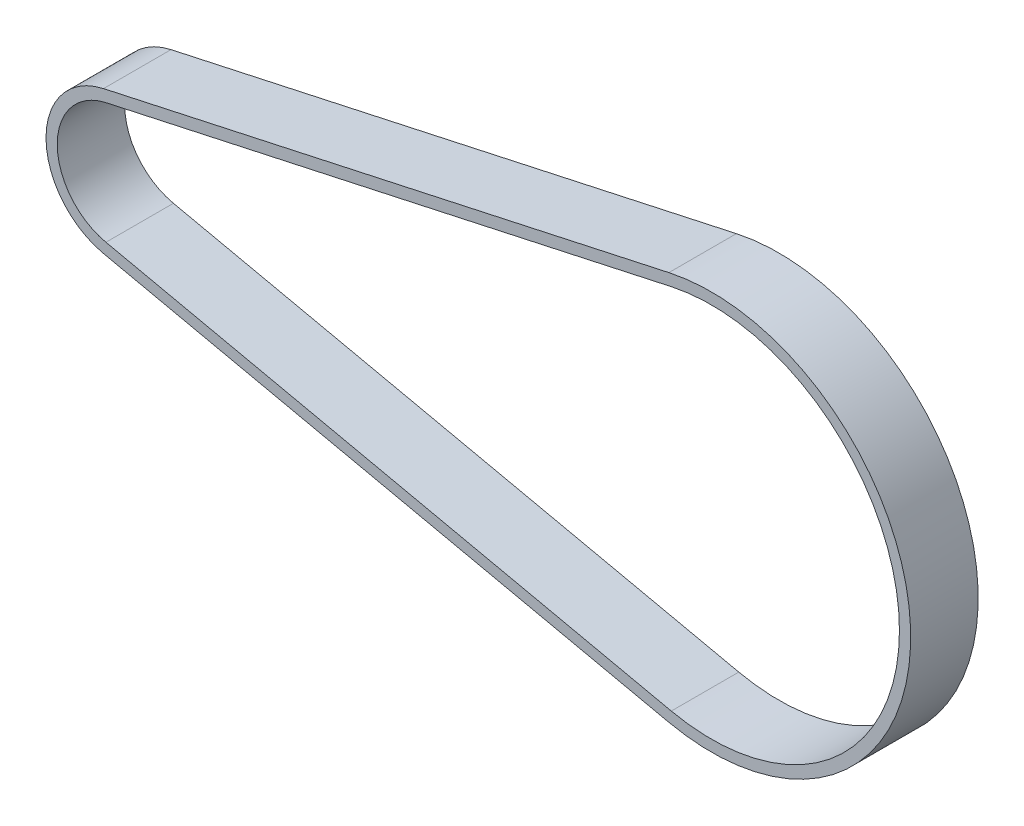
SolidWorks part; units mm, degrees
material "HYPALON"
ref_plane "Alzado" through (0, 0, 0) normal (0, 0, 1) x (1, 0, 0)
ref_plane "Planta" through (0, 0, 0) normal (0, 1, 0) x (1, 0, 0)
ref_plane "Vista lateral" through (0, 0, 0) normal (1, 0, 0) x (0, 0, -1)
sketch "Croquis1" plane through (0, 0, 0) normal (0, 0, 1) x (1, 0, 0)
  line L0 (-1.1721, 5.3737) -> (49.0869, 16.3359)
  line L1 (-1.1721, -5.3737) -> (49.0869, -16.3359)
  line L2 (-1.3852, 6.3507) -> (48.8738, 17.313)
  line L3 (-1.3852, -6.3507) -> (48.8738, -17.313)
  arc A0 (-1.1721, 5.3737) -> (-1.1721, -5.3737) centre (0, 0) ccw
  arc A1 (49.0869, -16.3359) -> (49.0869, 16.3359) centre (52.65, 0) ccw
  arc A2 (48.8738, -17.313) -> (48.8738, 17.313) centre (52.65, 0) ccw
  arc A3 (-1.3852, 6.3507) -> (-1.3852, -6.3507) centre (0, 0) ccw
  dimension "D1" = 11
  dimension "D2" = 33.44
  dimension "D3" = 52.65
  dimension "D4" = 1
extrude "Saliente-Extruir1" add sketch "Croquis1" along normal blind 6
